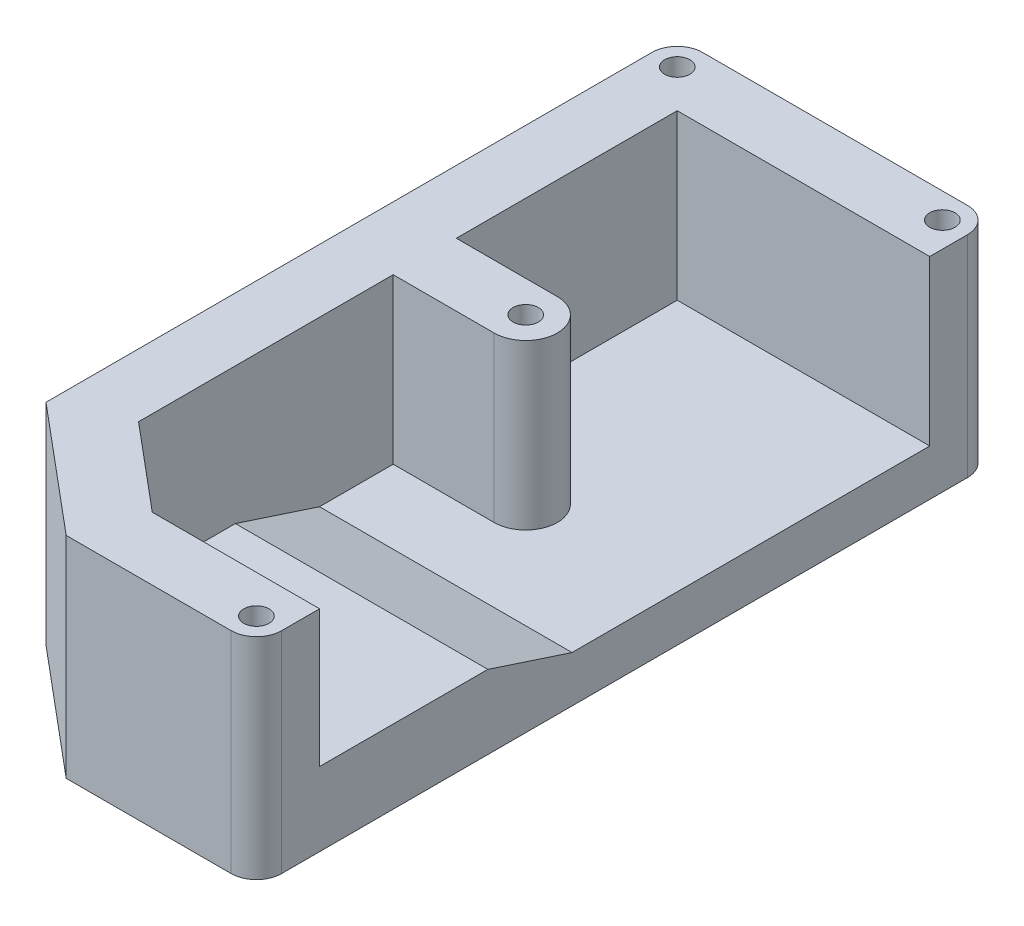
SolidWorks part; units mm, degrees
ref_plane "Front Plane" through (0, 0, 0) normal (0, 0, 1) x (1, 0, 0)
ref_plane "Top Plane" through (0, 0, 0) normal (0, 1, 0) x (1, 0, 0)
ref_plane "Right Plane" through (0, 0, 0) normal (1, 0, 0) x (0, 0, -1)
sketch "Sketch2" plane through (0, 0, 0) normal (0, 1, 0) x (1, 0, 0)
  line L0 (0, -150) -> (29.7938, -175)
  line L1 (6, 0) -> (69, 0)
  line L2 (0, -6) -> (0, -150)
  line L3 (29.7938, -175) -> (69, -175)
  line L4 (75, -6) -> (75, -169)
  arc A2 (69, -175) -> (75, -169) centre (69, -169) ccw
  arc A3 (69, 0) -> (75, -6) centre (69, -6) cw
  arc A4 (6, 0) -> (0, -6) centre (6, -6) ccw
  circle A5 centre (69, -169) radius 2
  circle A6 centre (69, -6) radius 2
  circle A7 centre (6, -6) radius 2
  circle A10 centre (39, -75) radius 2
  point P7 (29.7938, -175)
  point P8 (0, -150)
  point P10 (75, -175)
  point P13 (75, 0)
  point P16 (0, 0)
  dimension "D9" = 4
  dimension "D6" = 4
  dimension "D5" = 6
  dimension "D7" = 4
  dimension "D8" = 4
  dimension "D1" = 175
  dimension "D2" = 75
  dimension "D3" = 140
  dimension "D4" = 150
  dimension "D10" = 75
  dimension "D11" = 39
extrude "Boss-Extrude1" add sketch "Sketch2" along normal blind 11
sketch "Sketch3" plane through (0, 11, 0) normal (0, 1, 0) x (1, 0, 0)
  line L0 (39, -75) -> (37, -75) construction
  line L1 (15, -67.5) -> (39, -67.5)
  line L2 (15, -82.5) -> (39, -82.5)
  line L4 (15, -82.5) -> (15, -143.0054)
  line L5 (69, 0) -> (6, 0)
  line L6 (69, 0) -> (6, 0)
  line L7 (75, -15) -> (75, -6)
  line L8 (75, -169) -> (75, -6)
  line L9 (75, -169) -> (75, -160)
  line L11 (15, -82.5) -> (15, -143.0054)
  line L17 (75, -169) -> (75, -6)
  line L18 (69, 0) -> (6, 0)
  line L19 (0, -6) -> (0, -150)
  line L20 (0, -150) -> (29.7938, -175)
  line L21 (29.7938, -175) -> (69, -175)
  line L23 (69, 0) -> (6, 0)
  line L24 (0, -6) -> (0, -150)
  line L25 (0, -150) -> (29.7938, -175)
  line L26 (29.7938, -175) -> (69, -175)
  line L41 (75, -15) -> (15, -15)
  line L42 (15, -15) -> (15, -67.5)
  line L43 (15, -143.0054) -> (35.2534, -160)
  line L44 (35.2534, -160) -> (75, -160)
  arc A2 (39, -82.5) -> (39, -67.5) centre (39, -75) ccw
  circle A3 centre (39, -75) radius 2
  circle A4 centre (39, -75) radius 2
  arc A6 (69, -175) -> (75, -169) centre (69, -169) ccw
  arc A7 (75, -6) -> (69, 0) centre (69, -6) ccw
  arc A8 (6, 0) -> (0, -6) centre (6, -6) ccw
  arc A9 (69, -175) -> (75, -169) centre (69, -169) ccw
  arc A10 (75, -6) -> (69, 0) centre (69, -6) ccw
  arc A11 (6, 0) -> (0, -6) centre (6, -6) ccw
  circle A12 centre (6, -6) radius 2
  circle A13 centre (6, -6) radius 2
  circle A15 centre (69, -6) radius 2
  circle A16 centre (69, -6) radius 2
  circle A18 centre (69, -169) radius 2
  circle A19 centre (69, -169) radius 2
  circle M32 centre (6, -6) radius 2
  circle M33 centre (69, -6) radius 2
  arc M34 (69, -175) -> (75, -169) centre (69, -169) ccw
  line M35 (75, -169) -> (75, -6)
  arc M36 (75, -6) -> (69, 0) centre (69, -6) ccw
  line M37 (69, 0) -> (6, 0)
  arc M38 (6, 0) -> (0, -6) centre (6, -6) ccw
  line M39 (0, -6) -> (0, -150)
  line M40 (0, -150) -> (29.7938, -175)
  line M41 (29.7938, -175) -> (69, -175)
  circle M42 centre (69, -169) radius 2
  circle M43 centre (39, -75) radius 2
  dimension "D1" = 0
  dimension "D4" = 7.5
  dimension "D2" = 0
  dimension "D3" = 0
  dimension "D5" = 0
  dimension "D6" = 0
  dimension "D7" = 0
  dimension "D8" = 0
extrude "Boss-Extrude2" add sketch "Sketch3" along normal blind 39 contours L2 A2 L1 L42 L41 L44 L43 L4 M35 M36 M37 M38 M39 M40 M41 M34 M33 M42 M43 M32
sketch "Sketch4" plane through (75, 0, 0) normal (1, 0, 0) x (0, 0, -1)
  line L0 (-160, 17.5353) -> (-120, 17.5353)
  line L1 (-160, 50) -> (-160, 11) construction
  line L2 (-120, 17.5353) -> (-100, 11)
  dimension "D1" = 40
extrude "Extrude-Thin1" add sketch "Sketch4" against normal up to body separate body thin
sketch "Sketch5" plane through (0, 50, 0) normal (0, 1, 0) x (1, 0, 0)
  line L26 (15, -82.5) -> (39, -82.5)
  line L27 (39, -67.5) -> (15, -67.5)
  line L28 (15, -67.5) -> (15, -15)
  line L29 (15, -15) -> (75, -15)
  line L30 (75, -15) -> (75, -6)
  line L31 (69, 0) -> (6, 0)
  line L32 (0, -6) -> (0, -150)
  line L33 (0, -150) -> (29.7938, -175)
  line L34 (29.7938, -175) -> (69, -175)
  line L35 (75, -169) -> (75, -160)
  line L36 (75, -160) -> (35.2534, -160)
  line L37 (35.2534, -160) -> (15, -143.0054)
  line L38 (15, -143.0054) -> (15, -82.5)
  line L39 (15, -82.5) -> (39, -82.5)
  line L40 (39, -67.5) -> (15, -67.5)
  line L41 (15, -67.5) -> (15, -15)
  line L42 (15, -15) -> (75, -15)
  line L43 (75, -15) -> (75, -6)
  line L44 (69, 0) -> (6, 0)
  line L45 (0, -6) -> (0, -150)
  line L46 (0, -150) -> (29.7938, -175)
  line L47 (29.7938, -175) -> (69, -175)
  line L48 (75, -169) -> (75, -160)
  line L49 (75, -160) -> (35.2534, -160)
  line L50 (35.2534, -160) -> (15, -143.0054)
  line L51 (15, -143.0054) -> (15, -82.5)
  circle A6 centre (69, -6) radius 2
  circle A7 centre (69, -6) radius 2
  arc A8 (39, -82.5) -> (39, -67.5) centre (39, -75) ccw
  arc A9 (75, -6) -> (69, 0) centre (69, -6) ccw
  arc A10 (6, 0) -> (0, -6) centre (6, -6) ccw
  arc A11 (69, -175) -> (75, -169) centre (69, -169) ccw
  arc A12 (39, -82.5) -> (39, -67.5) centre (39, -75) ccw
  arc A13 (75, -6) -> (69, 0) centre (69, -6) ccw
  arc A14 (6, 0) -> (0, -6) centre (6, -6) ccw
  arc A15 (69, -175) -> (75, -169) centre (69, -169) ccw
  circle A17 centre (6, -6) radius 2
  circle A18 centre (6, -6) radius 2
  circle A20 centre (39, -75) radius 2
  circle A21 centre (39, -75) radius 2
  circle A22 centre (69, -6) radius 3
  circle A23 centre (69, -169) radius 2
  circle A24 centre (69, -169) radius 2
  circle A26 centre (6, -6) radius 3
  circle A27 centre (39, -75) radius 3
  circle A28 centre (69, -169) radius 3
  circle M22 centre (69, -6) radius 2
  circle M23 centre (69, -169) radius 2
  circle M24 centre (39, -75) radius 2
  circle M25 centre (6, -6) radius 2
  dimension "D6" = 6
  dimension "D1" = 0
  dimension "D2" = 0
  dimension "D3" = 0
  dimension "D4" = 0
  dimension "D5" = 0
extrude "Cut-Extrude2" cut sketch "Sketch5" against normal blind 6 contours A22 M22 | A26 M25 | A27 M24 | A28 M23 | A7
